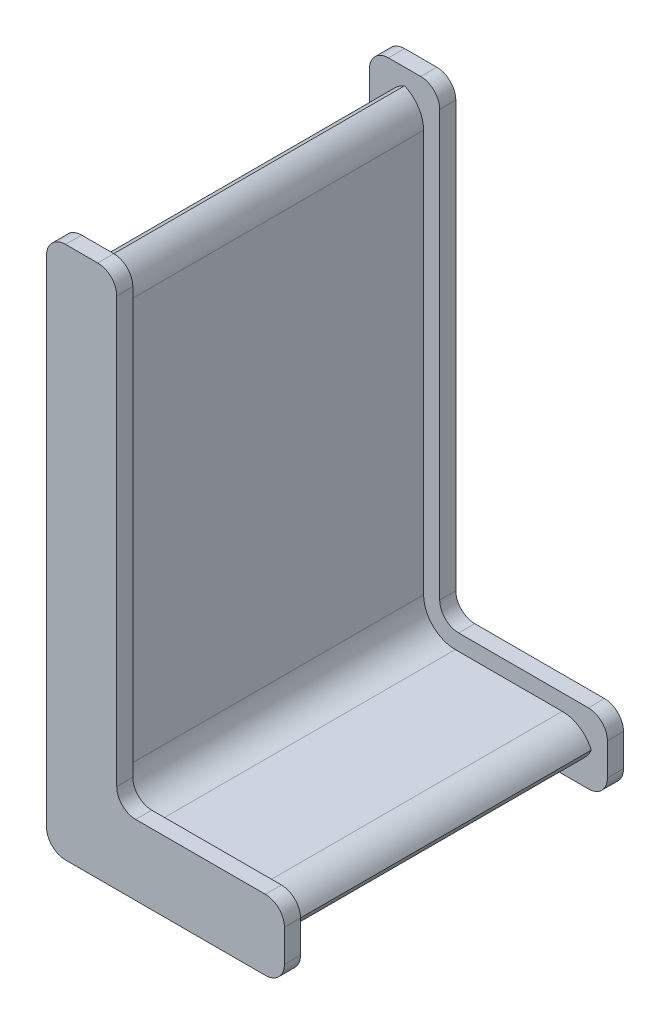
SolidWorks part; units mm, degrees
material "ABS"
ref_plane "X-Y Datum" through (0, 0, 0) normal (0, 0, 1) x (1, 0, 0)
ref_plane "X-Z Datum" through (0, 0, 0) normal (0, 1, 0) x (1, 0, 0)
ref_plane "Y-Z Datum" through (0, 0, 0) normal (1, 0, 0) x (0, 0, -1)
sketch "Sketch2" plane through (0, 0, 0) normal (0, 0, 1) x (1, 0, 0)
  line L0 (0, 5) -> (0, 74.46)
  line L3 (6, 0) -> (27.8774, 0)
  line L4 (5, 0) -> (6, 0)
  line L5 (6, 74.46) -> (6, 11)
  line L6 (11, 6) -> (27.8774, 6)
  arc A0 (11, 6) -> (6, 11) centre (11, 11) cw
  arc A1 (5, 0) -> (0, 5) centre (5, 5) cw
  arc A2 (3, 79.0426) -> (0, 74.46) centre (5, 74.46) ccw
  arc A3 (3, 79.0426) -> (6, 74.46) centre (1, 74.46) cw
  arc A4 (32.46, 3) -> (27.8774, 0) centre (27.8774, 5) cw
  arc A5 (32.46, 3) -> (27.8774, 6) centre (27.8774, 1) ccw
  point P12 (0, 0)
  dimension "D1" = 5
  dimension "D2" = 5
  dimension "D3" = 5
  dimension "D4" = 5
  dimension "D5" = 5
  dimension "D6" = 69.46
  dimension "D7" = 6
  dimension "D8" = 6
  dimension "D9" = 32.46
extrude "Boss-Extrude1" add sketch "Sketch2" along normal blind 48.42
sketch "Sketch3" plane through (0, 0, 48.42) normal (0, 0, 1) x (1, 0, 0)
  line L1 (-2.54, 81.5826) -> (8.54, 81.5826)
  line L4 (8.54, 81.5826) -> (8.54, 8.54)
  line L5 (6, 11) -> (6, 74.46) construction
  line L7 (27.8774, 6) -> (11, 6) construction
  line L10 (8.54, 8.54) -> (35, 8.54)
  line L11 (35, -2.54) -> (35, 8.54)
  line L12 (35, -2.54) -> (-2.54, -2.54)
  line L13 (-2.54, 81.5826) -> (-2.54, -2.54)
  dimension "D2" = 2.54
  dimension "D3" = 2.54
  dimension "D5" = 2.54
  dimension "D6" = 2.54
extrude "Boss-Extrude2" add sketch "Sketch3" along normal blind 2.54
sketch "Sketch4" plane through (0, 0, 0) normal (0, 0, -1) x (-1, 0, 0)
  line L0 (-35, -2.54) -> (2.54, -2.54)
  line L1 (-35, 8.54) -> (-8.54, 8.54)
  line L2 (-35, 8.54) -> (-35, -2.54)
  line L5 (-8.54, 81.5826) -> (2.54, 81.5826)
  line L6 (-8.54, 81.5826) -> (-8.54, 8.54)
  line L9 (2.54, -2.54) -> (2.54, 81.5826)
extrude "Boss-Extrude3" add sketch "Sketch4" along normal blind 2.54
fillet "Fillet1" radius 3 12 edges at (35, 8.54, -1.27) (35, -2.54, -1.27) (-2.54, -2.54, -1.27) (8.54, 8.54, -1.27) (8.54, 81.5826, -1.27) (-2.54, 81.5826, -1.27) (-2.54, 81.5826, 49.69) (8.54, 81.5826, 49.69) (8.54, 8.54, 49.69) (35, 8.54, 49.69) (35, -2.54, 49.69) (-2.54, -2.54, 49.69)
